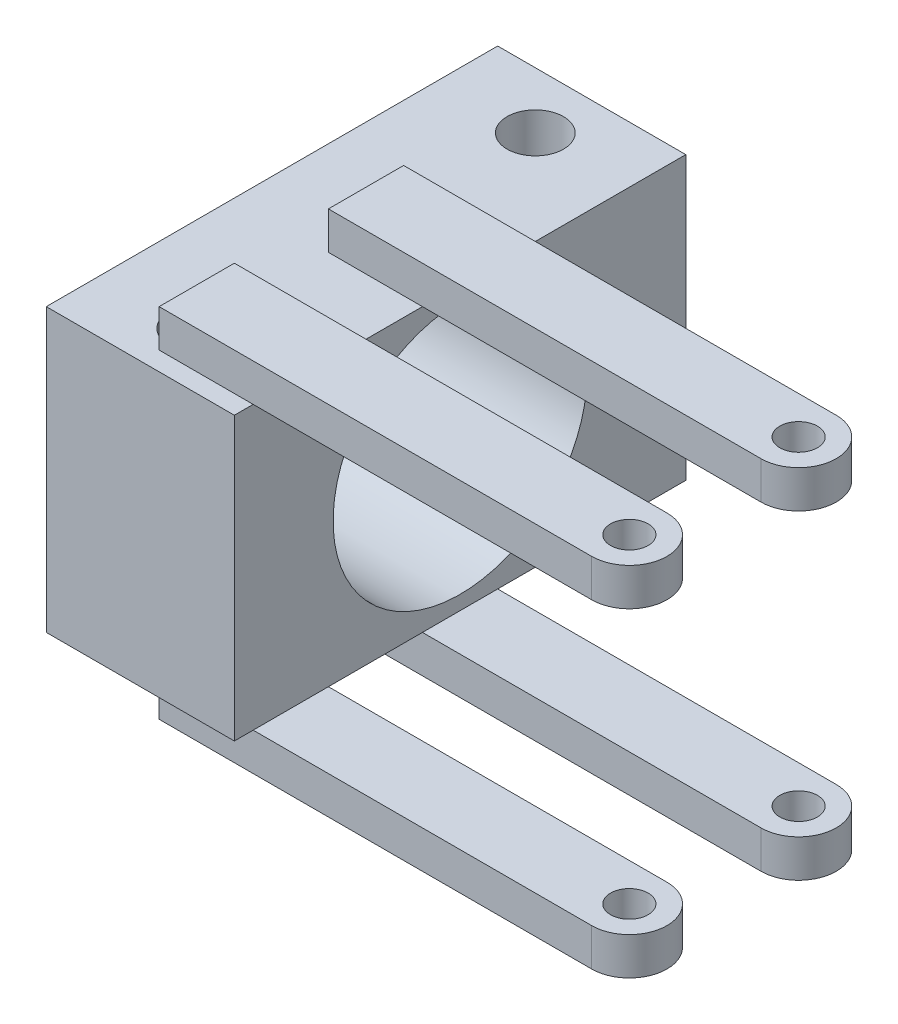
SolidWorks part; units mm, degrees
ref_plane "Front Plane" through (0, 0, 0) normal (0, 0, 1) x (1, 0, 0)
ref_plane "Top Plane" through (0, 0, 0) normal (0, 1, 0) x (1, 0, 0)
ref_plane "Right Plane" through (0, 0, 0) normal (1, 0, 0) x (0, 0, -1)
sketch "Sketch2" plane through (0, 0, 0) normal (0, 1, 0) x (1, 0, 0)
  line L0 (-5, 0) -> (5, 0) construction
  line L1 (-5, -12) -> (5, -12)
  line L2 (-5, -12) -> (-5, 12)
  line L3 (-5, 12) -> (5, 12)
  line L4 (5, -12) -> (5, 12)
  line L5 (-5, -12) -> (5, 12) construction
  line L6 (-5, 12) -> (5, -12) construction
  circle A0 centre (0, 9) radius 1.5
  circle A1 centre (0, -9) radius 1.5
  point P0 (0, 0)
  dimension "D3" = 3
  dimension "D1" = 10
  dimension "D2" = 24
  dimension "D4" = 9
extrude "Boss-Extrude1" add sketch "Sketch2" along normal blind 15
sketch "Sketch3" plane through (5, 0, 0) normal (1, 0, 0) x (0, 0, -1)
  line L0 (-12, 7.5) -> (12, 7.5) construction
  line L1 (-12, 15) -> (-12, 0) construction
  line L2 (12, 15) -> (12, 0) construction
  circle A0 centre (0, 7.5) radius 6.75
  dimension "D1" = 13.5
extrude "Cut-Extrude1" cut sketch "Sketch3" against normal up to surface (10 mm away) up to face at (-5, 7.5, 0)
sketch "Sketch5" plane through (0, 0, 0) normal (0, -1, 0) x (1, 0, 0)
  line L0 (0, 0) -> (23, 0) construction
  line L1 (0, 0) -> (0, 2)
  line L2 (0, 2) -> (23, 2)
  line L3 (23, 2) -> (23, 0) construction
  line L4 (23, 0) -> (23, -2) construction
  line L5 (23, -2) -> (0, -2)
  line L6 (0, -2) -> (0, 0)
  arc A0 (23, 2) -> (23, -2) centre (23, 0) cw
  circle A1 centre (23, 0) radius 1
  dimension "D3" = 2
  dimension "D1" = 23
  dimension "D2" = 2
extrude "Boss-Extrude2" add sketch "Sketch5" along normal blind 2
ref_plane "Plane1" through (0, 7.5, 0) normal (0, -1, 0) x (-1, 0, 0)
mirror "Mirror1" about plane through (0, 7.5, 0) normal (0, -1, 0) of "Boss-Extrude2"
ref_plane "Plane2" through (0, 0, 4.5) normal (0, 0, 1) x (1, 0, 0)
mirror "Mirror2" about plane through (0, 0, 4.5) normal (0, 0, 1) of "Mirror1", "Boss-Extrude2"
